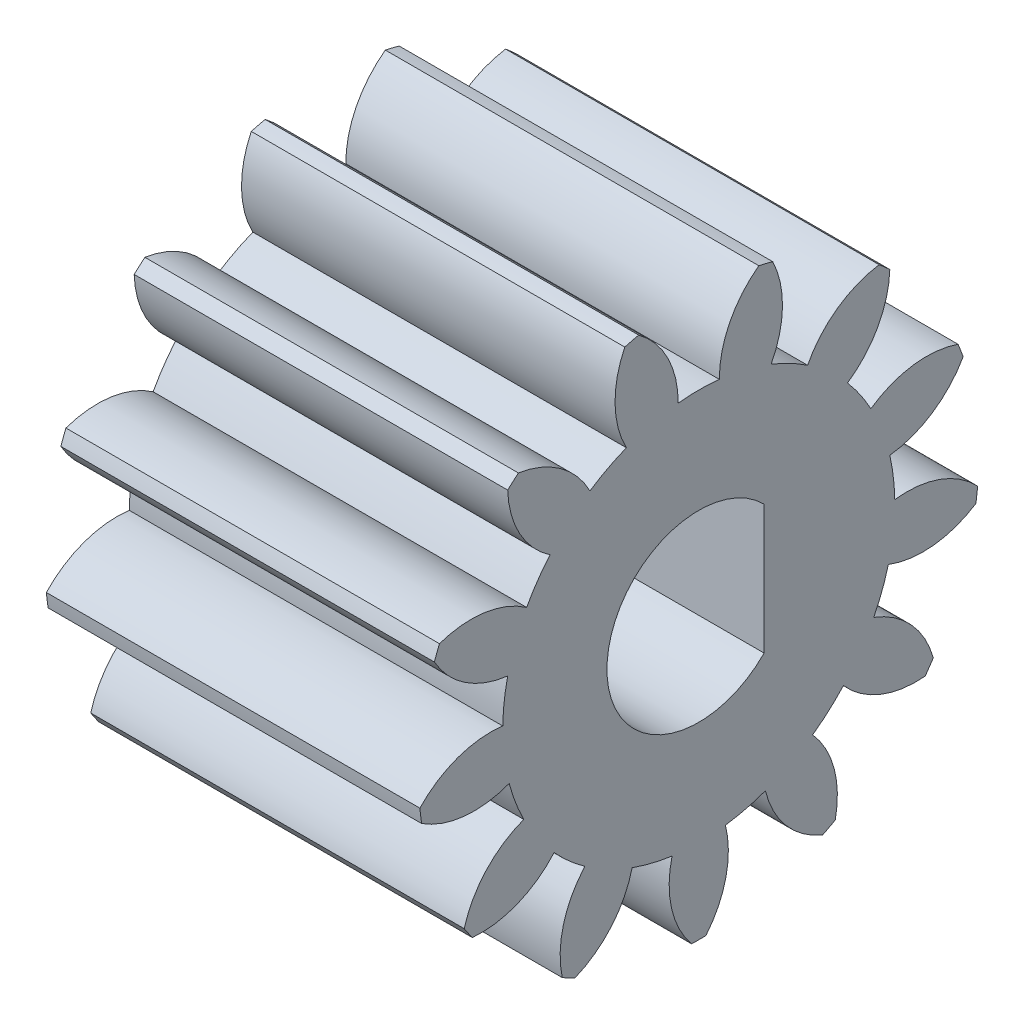
SolidWorks part; units mm, degrees
ref_plane "Plane1" through (0, 0, 0) normal (0, 0, 1) x (1, 0, 0)
ref_plane "Plane2" through (0, 0, 0) normal (0, 1, 0) x (1, 0, 0)
ref_plane "Plane3" through (0, 0, 0) normal (1, 0, 0) x (0, 0, -1)
sketch "HoldingSke" plane through (0, 0, 0) normal (0, 1, 0) x (1, 0, 0)
  line L0 (0, 0) -> (1.624, -0.3749)
  line L1 (-15, 0) -> (100, 0) construction
  line L2 (0, 0) -> (-2.1039, 2.3779)
  line L3 (0, 0) -> (-11.863, 4.5341)
  line L4 (0, 0) -> (8.4147, 1.9427)
  line L5 (0, 0) -> (-46.8476, -17.4728)
  line L6 (0, 0) -> (-1.8237, -1.2305)
  line L7 (-2.1039, 2.3779) -> (8.6586, 51.2061)
  line L8 (-76.2, 54.61) -> (-75.7, 54.61)
  line L9 (-71.009, 38.7566) -> (-53.1078, 45.2721)
  line L10 (-76.2, 71.12) -> (104.1128, 71.12)
  line L11 (0, 0) -> (-2.2, 0)
  line L12 (-76.2, 101.6) -> (-76.177, 101.6)
  line L13 (24.9733, 27.94) -> (52.9518, 28.4284)
  line L14 (24.9733, 27.94) -> (24.9743, 27.94)
  line L15 (24.9733, 27.94) -> (100.4006, 29.5858)
  line L16 (-63.627, -0.6) -> (-12.827, -0.6)
  circle A0 centre (0, 0) radius 1.5
  circle A1 centre (0, 0) radius 3.149
  circle A2 centre (0, 0) radius 37.5
  circle A3 centre (0, 0) radius 1.5
  dimension "MHD" = 6.298
  dimension "Hub_dia" = 75
  dimension "Bore" = 3
  dimension "MBD" = 3
  dimension "Num_teeth" = 13
  dimension "Pitch" = 1.6667
  dimension "Overall_len" = 50
  dimension "Show_teeth" = 13
  dimension "Thickness" = 2.2
  dimension "OAL" = 50.0003
  dimension "T_dim" = 0.5
  dimension "Ap" = 20
  dimension "H" = 19.05
  dimension "Pitch_radius" = 180.3128
  dimension "Width" = 2.2
  dimension "Backlash" = 0.023
  dimension "Addendum_fac" = 1
  dimension "Dedendum_fac" = 1.25
  dimension "Clearance_fac" = 0.25
  dimension "Dedendum_add" = 0.001
  dimension "Module" = 0.6
sketch "BasProSke" plane through (0, 0, 0) normal (0, 1, 0) x (1, 0, 0)
  line L0 (-10, 0) -> (60, 0) construction
  line L1 (0, 0) -> (0, 4.5)
  line L2 (0, 0) -> (6, 0)
  line L3 (6, 0) -> (6, 4.5)
  line L4 (6, 4.5) -> (0, 4.5)
  dimension "Thickness" = 6
  dimension "Diameter" = 9
revolve "Base-Revolve" add sketch "BasProSke" angle 360 about L0
sketch "TooCutSke" plane through (0, 0, 0) normal (1, 0, 0) x (0, 0, -1)
  line L1 (0, 0) -> (0, 107) construction
  line L2 (0, 0) -> (-0.5103, 3.8665) construction
  line L3 (0, 0) -> (-1.8553, 7.5272) construction
  line L4 (-0.5103, 3.8665) -> (-0.9276, 3.7636) construction
  arc A0 (0.3306, 3.1316) -> (-0.3306, 3.1316) centre (0, 0) ccw
  arc A1 (0.9926, 4.4152) -> (-0.9926, 4.4152) centre (0, 0) ccw
  circle A2 centre (0, 0) radius 3.9 construction
  circle A3 centre (0, 0) radius 3.6648 construction
  arc A4 (-0.3306, 3.1316) -> (-0.9926, 4.4152) centre (-1.8906, 3.1395) ccw
  arc A5 (0.9926, 4.4152) -> (0.3306, 3.1316) centre (1.8906, 3.1395) ccw
  dimension "Root_dia" = 6.298
  dimension "Overcut_dia" = 9.0508
  dimension "Pitch_dia" = 7.8
  dimension "Base_dia" = 7.3296
  dimension "Flank_rad" = 1.56
  dimension "Half_ang" = 13.846
  dimension "Half_CT" = 0.4298
extrude "ToothCut" cut sketch "TooCutSke" along normal through all
sketch "Sketch1" plane through (0, 0, 0) normal (-1, 0, 0) x (0, 0, 1)
  line L0 (-1.05, 1.0359) -> (-1.05, -1.0359)
  circle A0 centre (0, 0) radius 1.475 construction
  arc A1 (-1.05, -1.0359) -> (-1.05, 1.0359) centre (0, 0) ccw
  dimension "D1" = 2.95
  dimension "D2" = 1.05
fillet "Breaks" [suppressed] radius 0.012
fillet "RootFillets" [suppressed] radius 0.151
pattern_circular "TeethCuts" count 13 over 360 about axis through (0, 0, 0) along (1, 0, 0) of "ToothCut", "RootFillets", "Breaks"
sketch "HubNeaOneSke" plane through (0, 0, 0) normal (-1, 0, 0) x (0, 0, 1)
  circle A0 centre (0, 0) radius 3.149
  dimension "Diameter" = 6.298
extrude "HubNearOne" [suppressed] add sketch "HubNeaOneSke" along normal blind 44.0003
sketch "HubNeaBotSke" plane through (0, 0, 0) normal (-1, 0, 0) x (0, 0, 1)
  circle A0 centre (0, 0) radius 3.149
  dimension "Diameter" = 6.298
extrude "HubNearBoth" [suppressed] add sketch "HubNeaBotSke" along normal blind 22.0002
ref_plane "FarPln" through (6, 0, 0) normal (1, 0, 0) x (0, 0, -1)
sketch "HubFarSke" plane through (6, 0, 0) normal (1, 0, 0) x (0, 0, -1)
  circle A0 centre (0, 0) radius 3.149
  dimension "Diameter" = 6.298
extrude "HubFar" [suppressed] add sketch "HubFarSke" along normal blind 22.0002
sketch "KeySke" plane through (0, 0, 0) normal (1, 0, 0) x (0, 0, -1)
  line L0 (-0.6, 0) -> (-0.6, 2)
  line L1 (-0.6, 2) -> (0.6, 2)
  line L2 (0.6, 2) -> (0.6, 0)
  line L3 (0, 0) -> (0, 34) construction
  line L4 (-0.6, 0) -> (0.6, 0)
  dimension "Offset" = 2
  dimension "Width" = 1.2
extrude "Keyway" [suppressed] cut sketch "KeySke" along normal mid plane 100.0006
pattern_circular "Keyway2" [suppressed] count 2 every 90 about axis through (-10, 0, 0) along (1, 0, 0)
extrude "Cut-Extrude1" cut sketch "Sketch1" against normal up to next
equation "' \"Module@HoldingSke\" = 6.35"
equation "' \"Num_teeth@HoldingSke\" = 12"
equation "' \"Ap@HoldingSke\" =  20"
equation "' \"Ap@HoldingSke\" = 20"
equation "' \"Width@HoldingSke\" = 0.5 * 25.4"
equation "' \"Hub_dia@HoldingSke\"= 1 * 25.4"
equation "' \"Hub_dia@HoldingSke\" = 1 * 25.4"
equation "' \"Overall_len@HoldingSke\" = 1.0 * 25.4"
equation "' \"Bore@HoldingSke\" = 0.75 * 25.4"
equation "' \"T_dim@HoldingSke\" = 0.1 * 25.4"
equation "' \"Width@KeySke\" = 0.25 * 25.4"
equation "' \"Show_teeth@HoldingSke\" = 13"
equation "' \"Backlash@HoldingSke\" = 0.009 * 25.4"
equation "' \"Addendum_fac@HoldingSke\" = 1.0"
equation "' \"Dedendum_fac@HoldingSke\" = 1.25"
equation "' \"Dedendum_add@HoldingSke\" = 0.00005 * 25.4"
equation "' \"Clearance_fac@HoldingSke\" = 0.25"
equation "\"Pitch@HoldingSke\" = 1 / \"Module@HoldingSke\""
equation "\"Overcut_dia@TooCutSke\" = (\"Num_teeth@HoldingSke\" + 2 * \"Addendum_fac@HoldingSke\") / \"Pitch@HoldingSke\" + 0.002 * 25.4"
equation "\"Pitch_dia@TooCutSke\" = \"Num_teeth@HoldingSke\" / \"Pitch@HoldingSke\""
equation "\"Base_dia@TooCutSke\" = \"Num_teeth@HoldingSke\" / \"Pitch@HoldingSke\" * cos((\"Ap@HoldingSke\"  * 3.14159265 / 180))"
equation "\"Root_dia@TooCutSke\" = (\"Num_teeth@HoldingSke\" + 2) / \"Pitch@HoldingSke\" - 2 * (\"Addendum_fac@HoldingSke\" + \"Dedendum_fac@HoldingSke\") / \"Pitch@HoldingSke\" - \"Dedendum_add@HoldingSke\" * 2"
equation "\"Half_ang@TooCutSke\" = 180 / \"Num_teeth@HoldingSke\""
equation "\"Half_CT@TooCutSke\" = \"Num_teeth@HoldingSke\" / \"Pitch@HoldingSke\" * sin((3.14159265 / 2 / \"Num_teeth@HoldingSke\")) / 2 - 7 * \"Backlash@HoldingSke\" / 4"
equation "\"Flank_rad@TooCutSke\" = \"Num_teeth@HoldingSke\" / \"Pitch@HoldingSke\" / 5"
equation "\"Radius@RootFillets\" = \"Clearance_fac@HoldingSke\" / \"Pitch@HoldingSke\" + \"Dedendum_add@HoldingSke\""
equation "\"Break_rad@Breaks\" = 0.02 / \"Pitch@HoldingSke\""
equation "\"Thickness@HoldingSke\" = \"Width@HoldingSke\""
equation "\"OAL@HoldingSke\" = \"Thickness@HoldingSke\""
equation "\"MHD@HoldingSke\" = (\"Num_teeth@HoldingSke\" + 2) / \"Pitch@HoldingSke\" - 2 * (\"Addendum_fac@HoldingSke\" + \"Dedendum_fac@HoldingSke\")  / \"Pitch@HoldingSke\" - \"Dedendum_add@HoldingSke\" * 2"
equation "\"MBD@HoldingSke\" = (\"Num_teeth@HoldingSke\" + 2) / \"Pitch@HoldingSke\" - 2 * (\"Addendum_fac@HoldingSke\" + \"Dedendum_fac@HoldingSke\")  / \"Pitch@HoldingSke\" - \"Dedendum_add@HoldingSke\" * 2 - 0.002 * 25.4"
equation "\"MHD@HoldingSke\" = ((sgn( \"MHD@HoldingSke\" - \"Hub_dia@HoldingSke\" )-1)*( \"MHD@HoldingSke\" - \"Hub_dia@HoldingSke\" ))/-2+ \"Hub_dia@HoldingSke\""
equation "\"MBD@HoldingSke\" = ((sgn( \"MBD@HoldingSke\" - \"Bore@HoldingSke\" )-1)*( \"MBD@HoldingSke\" - \"Bore@HoldingSke\" ))/-2+ \"Bore@HoldingSke\""
equation "\"OAL@HoldingSke\" = ((sgn( \"OAL@HoldingSke\" - \"Overall_len@HoldingSke\" )+1)*( \"OAL@HoldingSke\" - \"Overall_len@HoldingSke\" ))/2 + \"Overall_len@HoldingSke\" + 0.000002 * 25.4"
equation "\"Num_teeth@TeethCuts\" = int( \"Show_teeth@HoldingSke\" ) + 1"
equation "\"Num_teeth@TeethCuts\" = ((sgn( \"Num_teeth@TeethCuts\" - \"Num_teeth@HoldingSke\" )-1)*( \"Num_teeth@TeethCuts\" - \"Num_teeth@HoldingSke\" ))/-2+ \"Num_teeth@HoldingSke\""
equation "\"Num_teeth@TeethCuts\" = ((sgn( \"Num_teeth@TeethCuts\" - 2.0)+1)*( \"Num_teeth@TeethCuts\" - 2.0))/2 +2.0"
equation "\"Angle@TeethCuts\" = 360.0 / \"Num_teeth@HoldingSke\""
equation "\"Diameter@BasProSke\" = (\"Num_teeth@HoldingSke\" + 2 * \"Addendum_fac@HoldingSke\") / \"Pitch@HoldingSke\""
equation "' \"Fillet_rad@BasProSke\" =  \"Thickness@HoldingSke\" * 0.05"
equation "' \"Fillet_rad@BasProSke\" = \"Thickness@HoldingSke\" * 0.05"
equation "\"MHD@HoldingSke\" = ((sgn( \"MHD@HoldingSke\" - \"Root_dia@TooCutSke\" )-1)*( \"MHD@HoldingSke\" - \"Root_dia@TooCutSke\" ))/-2+ \"Root_dia@TooCutSke\""
equation "\"Diameter@HubNeaOneSke\" = \"MHD@HoldingSke\""
equation "\"Length@HubNearOne\" = \"OAL@HoldingSke\" - \"Thickness@BasProSke\""
equation "\"Diameter@HubNeaBotSke\" = \"MHD@HoldingSke\""
equation "\"Length@HubNearBoth\" = ( \"OAL@HoldingSke\" - \"Thickness@BasProSke\" ) / 2.0"
equation "\"Thickness@FarPln\" = \"Thickness@BasProSke\""
equation "\"Diameter@HubFarSke\" = \"MHD@HoldingSke\""
equation "\"Length@HubFar\" = ( \"OAL@HoldingSke\" - \"Thickness@BasProSke\" ) / 2.0"
equation "\"D1@Keyway\" = \"OAL@HoldingSke\" * 2.0"
equation "\"Offset@KeySke\" = \"T_dim@HoldingSke\" + \"MBD@HoldingSke\" / 2.0"
